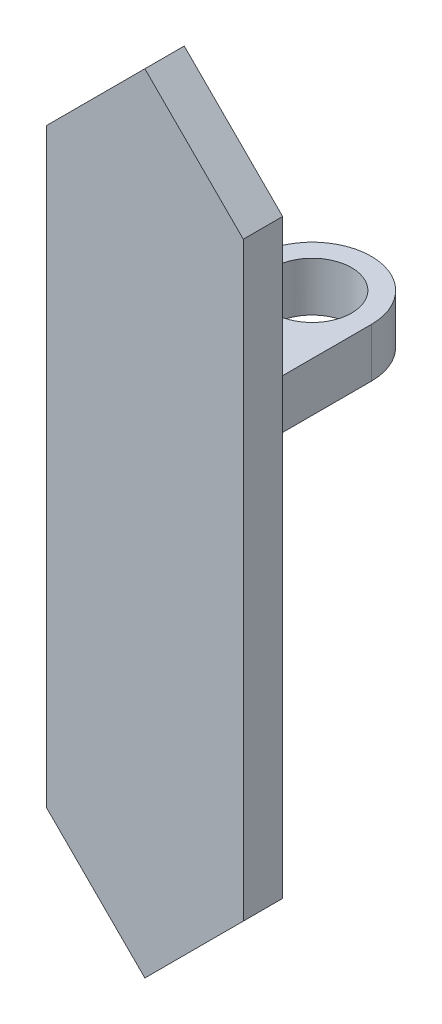
SolidWorks part; units mm, degrees
ref_plane "前视基准面" through (0, 0, 0) normal (0, 0, 1) x (1, 0, 0)
ref_plane "上视基准面" through (0, 0, 0) normal (0, 1, 0) x (1, 0, 0)
ref_plane "右视基准面" through (0, 0, 0) normal (1, 0, 0) x (0, 0, -1)
sketch "草图1" plane through (0, 0, 0) normal (0, 0, 1) x (1, 0, 0)
  line L2 (0.1473, 10) -> (0.1473, 70)
  line L4 (20.1473, 10) -> (20.1473, 70)
  line L5 (0.1473, 70) -> (10.1473, 80)
  line L6 (10.1473, 80) -> (20.1473, 70)
  line L8 (10.1473, 0) -> (20.1473, 10)
  line L9 (0.1473, 10) -> (10.1473, 0)
extrude "凸台-拉伸1" add sketch "草图1" along normal blind 4 contours L2 L9 L8 L4 L6 L5
sketch "草图2" plane through (0, 0, 0) normal (0, 0, -1) x (-1, 0, 0)
  line L0 (-10.1473, 52) -> (-10.1473, 80)
  line L5 (-16.1473, 52) -> (-4.1473, 52)
  line L6 (-16.1473, 52) -> (-16.1473, 47)
  line L7 (-16.1473, 47) -> (-4.1473, 47)
  line L8 (-4.1473, 52) -> (-4.1473, 47)
  line L9 (-16.1473, 52) -> (-4.1473, 47) construction
  line L10 (-16.1473, 47) -> (-4.1473, 52) construction
  point P8 (-10.1473, 49.5)
  dimension "D1" = 28
extrude "凸台-拉伸2" add sketch "草图2" along normal blind 20 contours L8 L5 L6 L7
sketch "草图6" plane through (0, 47, 0) normal (0, -1, 0) x (1, 0, 0)
  line L0 (10.1473, -13) -> (10.1473, 0)
  line L1 (16.1473, 0) -> (4.1473, 0) construction
  circle A0 centre (10.1473, -13) radius 6
  circle A1 centre (10.1473, -13) radius 4
  dimension "D1" = 13
extrude "切除-拉伸5" cut sketch "草图6" against normal blind 21
